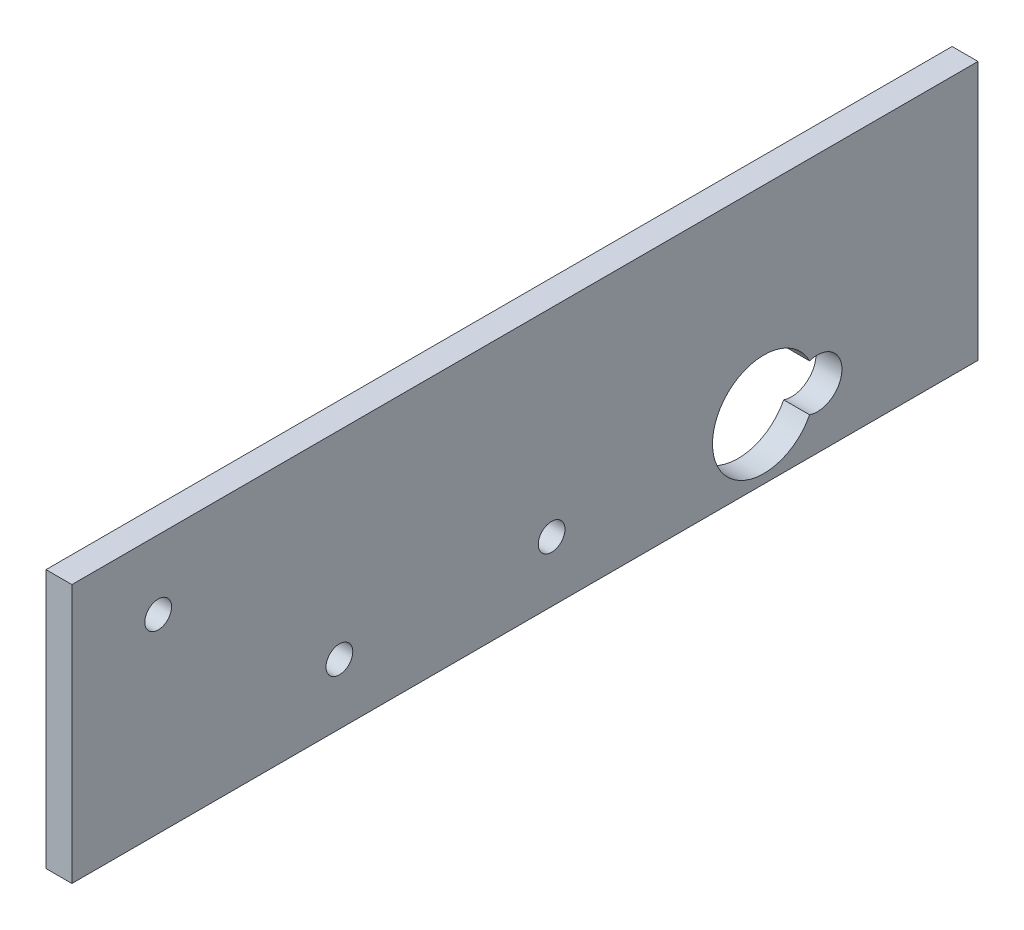
SolidWorks part; units mm, degrees
ref_plane "Ebene vorne" through (0, 0, 0) normal (0, 0, 1) x (1, 0, 0)
ref_plane "Ebene oben" through (0, 0, 0) normal (0, 1, 0) x (1, 0, 0)
ref_plane "Ebene rechts" through (0, 0, 0) normal (1, 0, 0) x (0, 0, -1)
sketch "Skizze1" plane through (0, 0, 0) normal (1, 0, 0) x (0, 0, -1)
  line L1 (0, 0) -> (105, 0)
  line L2 (0, 0) -> (0, 30)
  line L3 (0, 30) -> (105, 30)
  line L4 (105, 0) -> (105, 30)
  dimension "D1" = 105
  dimension "D2" = 30
extrude "Aufsatz-Linear austragen1" add sketch "Skizze1" along normal blind 3
sketch "Skizze2" plane through (3, 0, 0) normal (1, 0, 0) x (0, 0, -1)
  line L0 (10, 0) -> (10, 22) construction
  line L1 (0, 0) -> (105, 0) construction
  line L2 (31, 0) -> (31, 7) construction
  line L3 (55.5919, 0) -> (55.5919, 7) construction
  line L4 (80.1837, 0) -> (80.1837, 7) construction
  line L5 (80.1837, 7) -> (55.5919, 7) construction
  line L6 (55.5919, 7) -> (31, 7) construction
  line L7 (0, 30) -> (0, 0) construction
  circle A0 centre (10, 22) radius 1.55
  circle A1 centre (31, 7) radius 1.55
  circle A2 centre (55.5919, 7) radius 1.55
  circle A3 centre (80.1837, 7) radius 1.55
  dimension "D6" = 3.1
  dimension "D1" = 21
  dimension "D3" = 15
  dimension "D4" = 7
  dimension "D5" = 10
  dimension "D7" = 49.1837
extrude "Bohrungen" cut sketch "Skizze2" against normal through all
sketch "Skizze7" plane through (0, 0, 0) normal (1, 0, 0) x (0, 0, -1)
  line L0 (91.2182, 7) -> (69.8307, 7) construction
  line L1 (80.1837, 12.8805) -> (80.1837, 0.9323) construction
  arc A0 (85.4837, 9.7042) -> (85.4837, 4.2958) centre (80.1837, 7) ccw
  arc A1 (85.4837, 4.2958) -> (85.4837, 9.7042) centre (86.3837, 7) ccw
  point P9 (0, 0)
  point P10 (0, 0)
  dimension "D1" = 11.9
  dimension "D2" = 5.7
  dimension "D3" = 6.2
extrude "Schnitt-Linear austragen4" cut sketch "Skizze7" along normal up to surface (3 mm away) up to face at (3, 22, -11.55)
